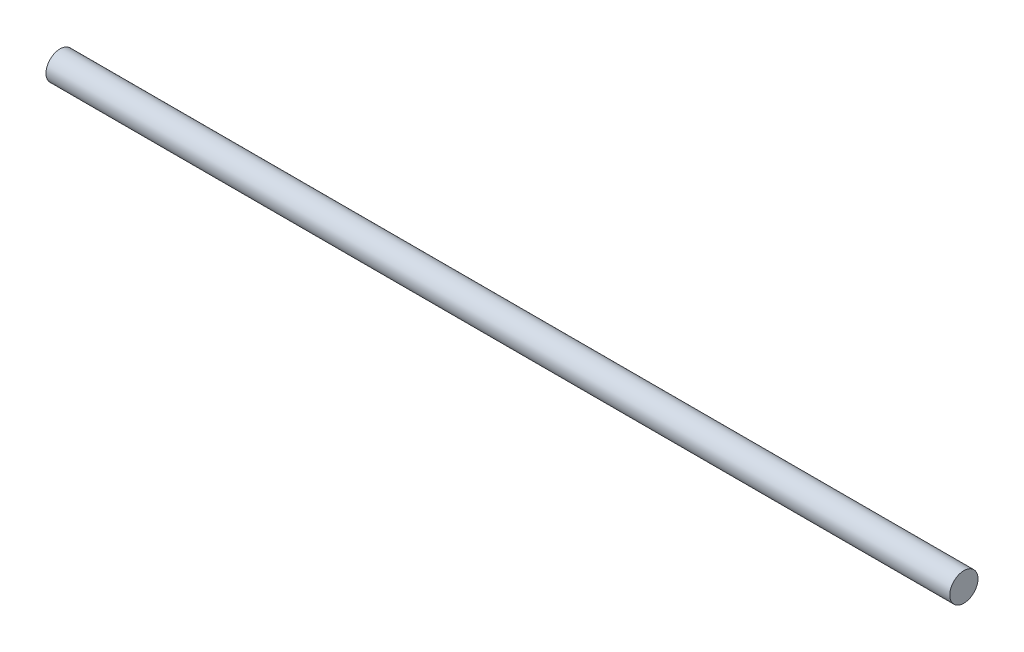
SolidWorks part; units mm, degrees
material "Hexcel AS4C (3000 Filaments)"
ref_plane "Front Plane" through (0, 0, 0) normal (0, 0, 1) x (1, 0, 0)
ref_plane "Top Plane" through (0, 0, 0) normal (0, 1, 0) x (1, 0, 0)
ref_plane "Right Plane" through (0, 0, 0) normal (1, 0, 0) x (0, 0, -1)
sketch "Sketch1" plane through (0, 0, 0) normal (1, 0, 0) x (0, 0, -1)
  circle A0 centre (0, 0) radius 1.25
  dimension "D1" = 2.5
extrude "Boss-Extrude1" add sketch "Sketch1" along normal blind 80
